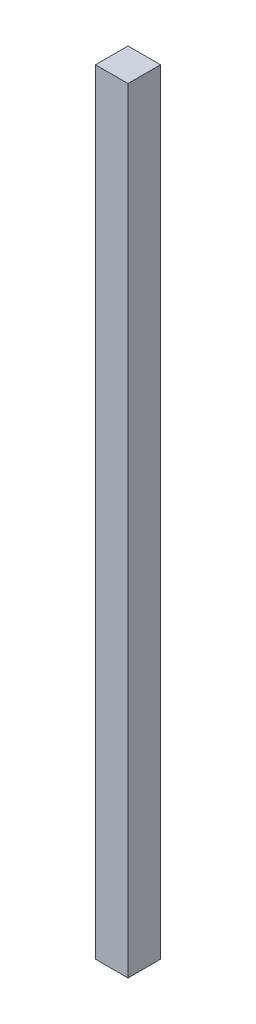
SolidWorks part; units mm, degrees
ref_plane "Front Plane" through (0, 0, 0) normal (0, 0, 1) x (1, 0, 0)
ref_plane "Top Plane" through (0, 0, 0) normal (0, 1, 0) x (1, 0, 0)
ref_plane "Right Plane" through (0, 0, 0) normal (1, 0, 0) x (0, 0, -1)
sketch "Sketch1" plane through (0, 0, 0) normal (0, 1, 0) x (1, 0, 0)
  line L1 (-5.244, 5.244) -> (5.244, 5.244)
  line L2 (-5.244, 5.244) -> (-5.244, -5.244)
  line L3 (-5.244, -5.244) -> (5.244, -5.244)
  line L4 (5.244, 5.244) -> (5.244, -5.244)
  line L5 (-5.244, 5.244) -> (5.244, -5.244) construction
  line L6 (-5.244, -5.244) -> (5.244, 5.244) construction
  point P0 (0, 0)
  dimension "D1" = 10.4881
  dimension "D2" = 10.4881
extrude "Boss-Extrude1" add sketch "Sketch1" along normal blind 250
